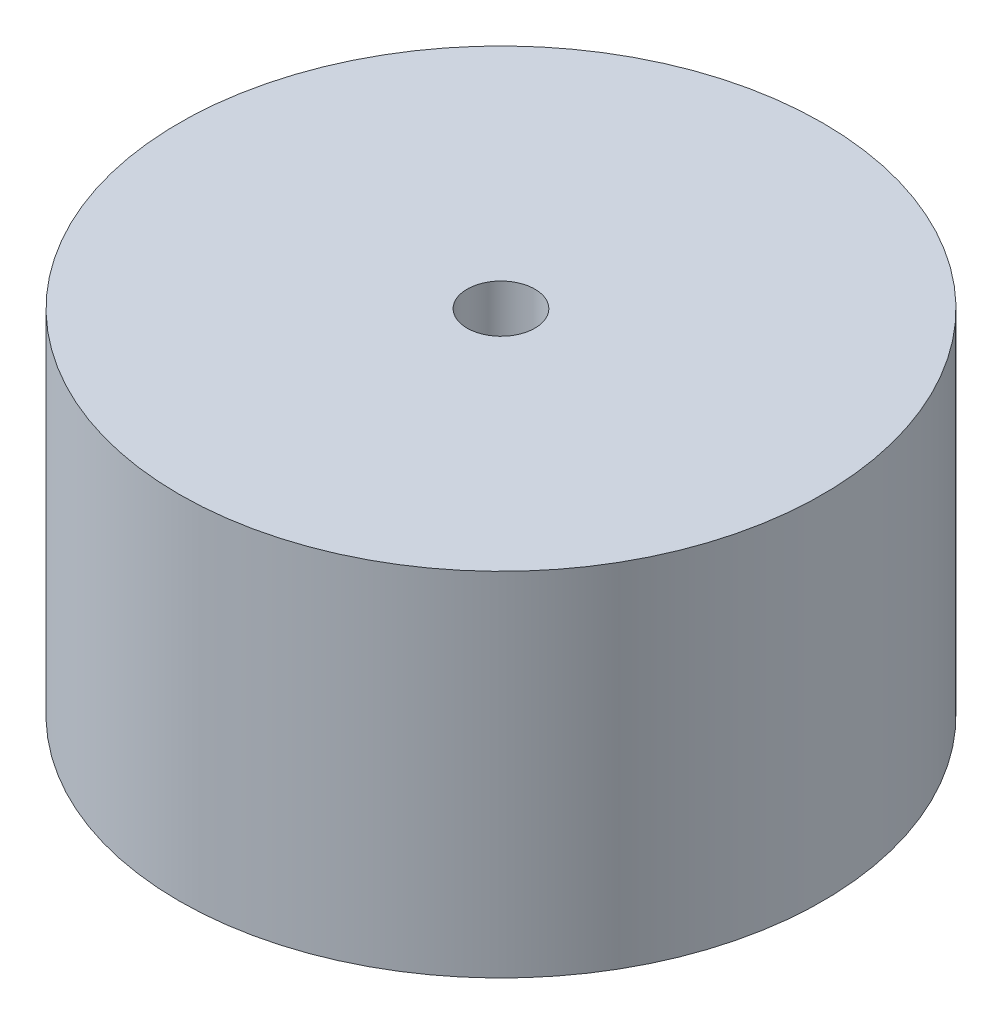
SolidWorks part; units mm, degrees
ref_plane "Alzado" through (0, 0, 0) normal (0, 0, 1) x (1, 0, 0)
ref_plane "Planta" through (0, 0, 0) normal (0, 1, 0) x (1, 0, 0)
ref_plane "Vista lateral" through (0, 0, 0) normal (1, 0, 0) x (0, 0, -1)
sketch "Croquis1" plane through (0, 0, 0) normal (0, 1, 0) x (1, 0, 0)
  circle A0 centre (0, 0) radius 15
  dimension "D1" = 30
extrude "Saliente-Extruir1" add sketch "Croquis1" along normal blind 4
sketch "Croquis2" plane through (0, 4, 0) normal (0, 1, 0) x (1, 0, 0)
  circle A0 centre (0, 0) radius 23.75
  dimension "D1" = 47.5
extrude "Saliente-Extruir2" add sketch "Croquis2" along normal blind 26
sketch "Croquis3" plane through (0, 30, 0) normal (0, 1, 0) x (1, 0, 0)
  circle A0 centre (0, 0) radius 2.5
  dimension "D1" = 5
extrude "Cortar-Extruir1" cut sketch "Croquis3" against normal blind 40
sketch "Croquis4" plane through (0, 30, 0) normal (0, 1, 0) x (1, 0, 0)
  circle A0 centre (0, 0) radius 20.8407
  circle A1 centre (0, 0) radius 9.2817
extrude "Cortar-Extruir3" cut sketch "Croquis4" against normal blind 19 from offset 3
